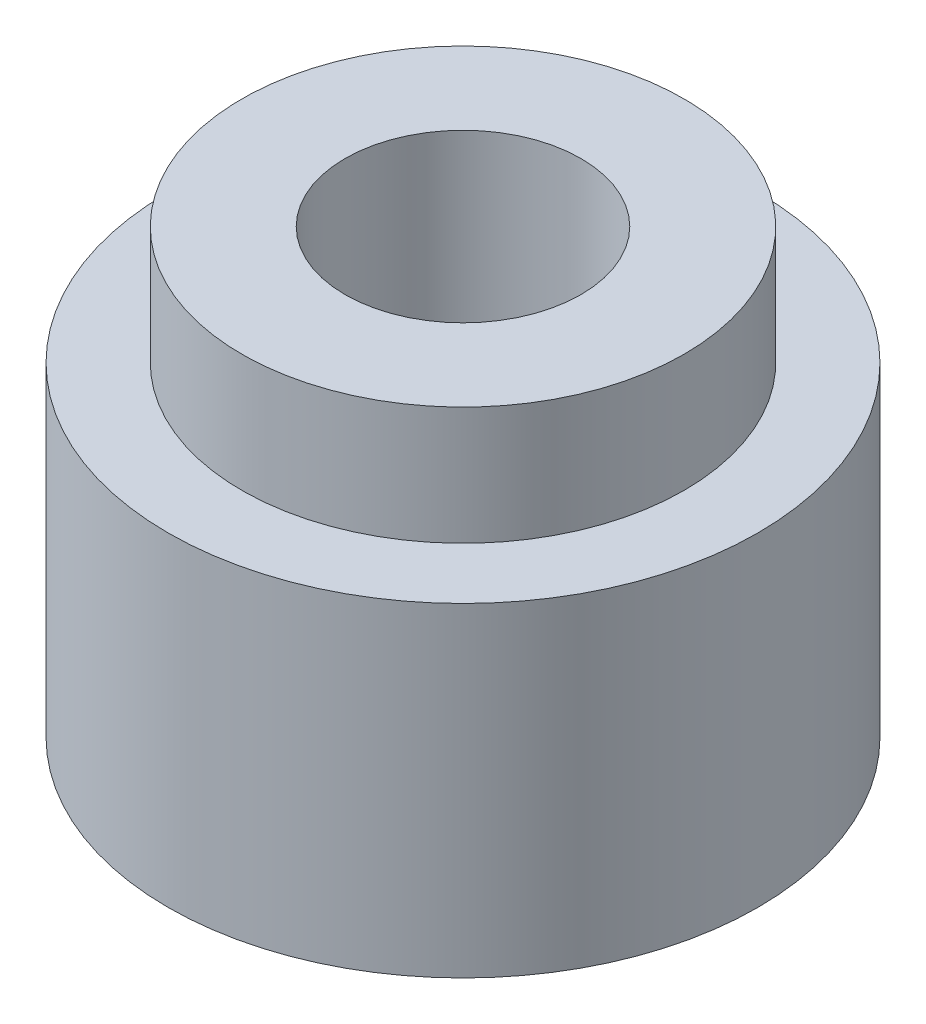
SolidWorks part; units mm, degrees
ref_plane "Front Plane" through (0, 0, 0) normal (0, 0, 1) x (1, 0, 0)
ref_plane "Top Plane" through (0, 0, 0) normal (0, 1, 0) x (1, 0, 0)
ref_plane "Right Plane" through (0, 0, 0) normal (1, 0, 0) x (0, 0, -1)
sketch "Sketch1" plane through (0, 0, 0) normal (0, 0, 1) x (1, 0, 0)
  line L0 (0, -1000) -> (0, 49000) construction
  line L1 (2.54, 0) -> (6.35, 0)
  line L2 (6.35, 0) -> (6.35, 6.985)
  line L3 (6.35, 6.985) -> (4.7625, 6.985)
  line L4 (4.7625, 6.985) -> (4.7625, 9.525)
  line L5 (4.7625, 9.525) -> (2.54, 9.525)
  line L6 (2.54, 9.525) -> (2.54, 0)
  dimension "D1" = 2.54
  dimension "D2" = 6.35
  dimension "D3" = 4.7625
  dimension "D4" = 6.985
  dimension "D5" = 2.54
revolve "Revolve1" add sketch "Sketch1" angle 360 about L0
